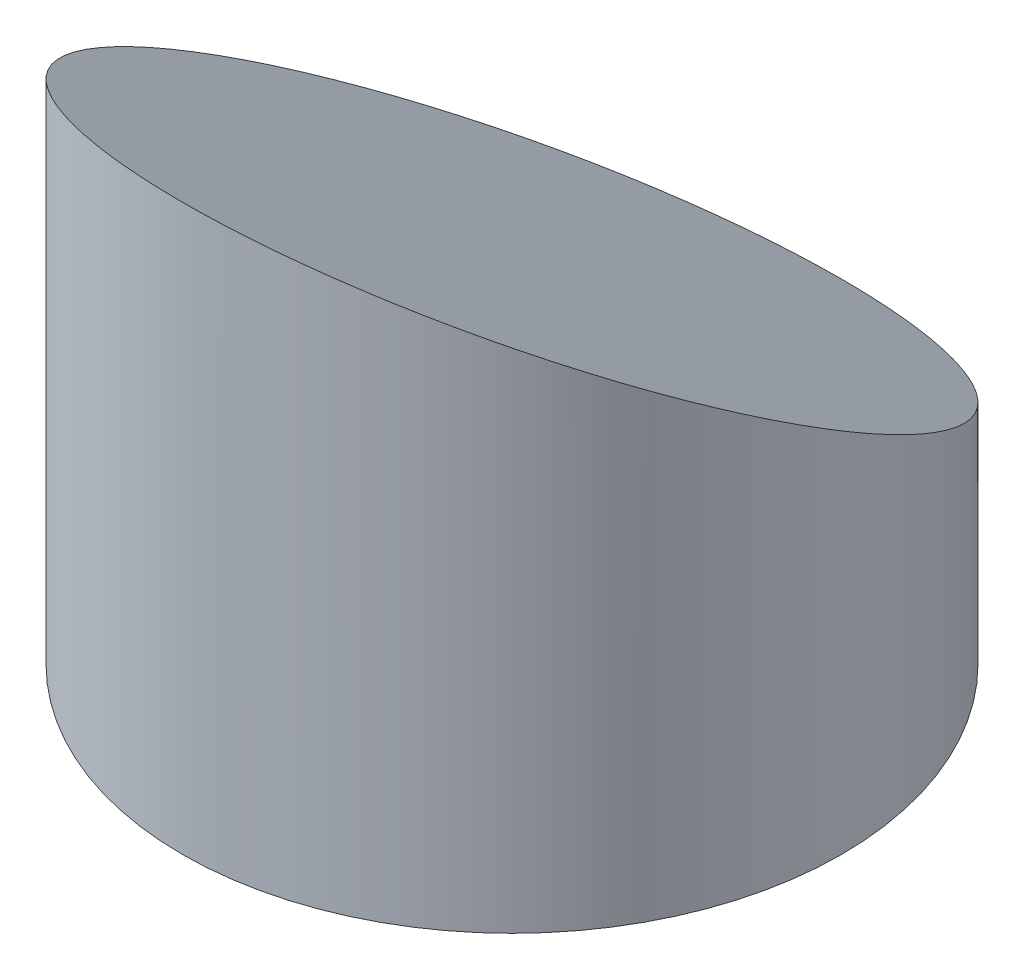
SolidWorks part; units mm, degrees
ref_plane "Front Plane" through (0, 0, 0) normal (0, 0, 1) x (1, 0, 0)
ref_plane "Top Plane" through (0, 0, 0) normal (0, 1, 0) x (1, 0, 0)
ref_plane "Right Plane" through (0, 0, 0) normal (1, 0, 0) x (0, 0, -1)
sketch "Sketch1" plane through (0, 0, 0) normal (0, 1, 0) x (1, 0, 0)
  circle A0 centre (0, 0) radius 3.5
  dimension "D1" = 7
extrude "Boss-Extrude1" add sketch "Sketch1" along normal blind 6
sketch "Sketch2" plane through (0, 0, 0) normal (1, 0, 0) x (0, 0, -1)
  line L0 (-3.5, 6) -> (3.5, 1.794)
  line L1 (3.5, 0) -> (3.5, 6) construction
  line L2 (3.5, 1.794) -> (-3.5, 1.794) construction
  line L3 (-3.5, 6) -> (-3.5, 0) construction
  point P5 (0, 0)
  point P9 (0, 0)
  dimension "D1" = 31
extrude "Cut-Extrude1" cut sketch "Sketch2" against normal through all both and the other way through all contours L0
